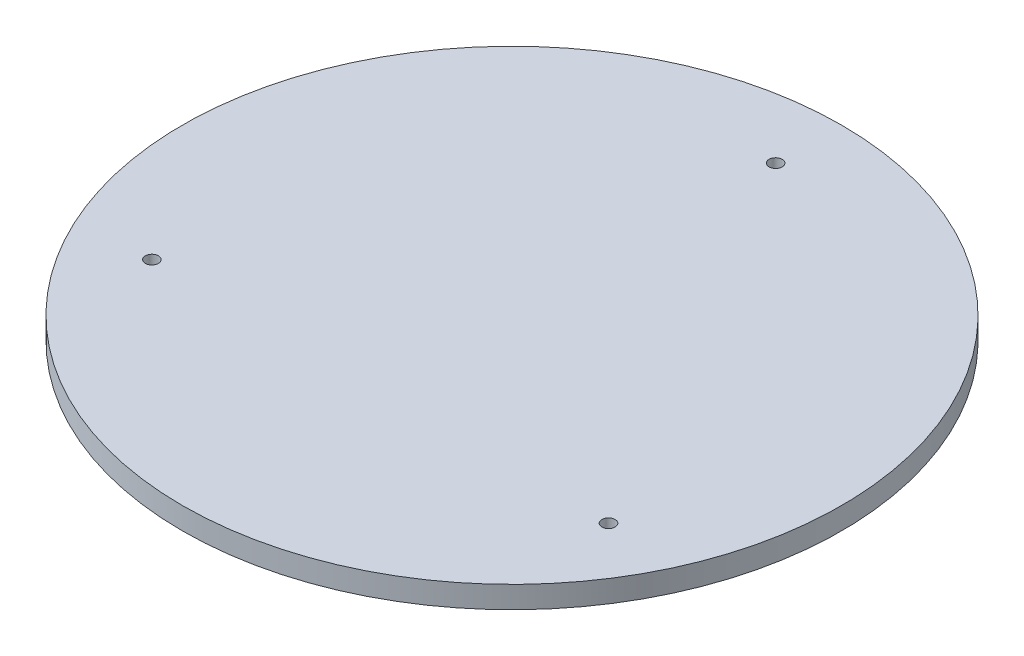
SolidWorks part; units mm, degrees
material "Alumina"
ref_plane "Front Plane" through (0, 0, 0) normal (0, 0, 1) x (1, 0, 0)
ref_plane "Top Plane" through (0, 0, 0) normal (0, 1, 0) x (1, 0, 0)
ref_plane "Right Plane" through (0, 0, 0) normal (1, 0, 0) x (0, 0, -1)
sketch "Sketch1" plane through (0, 0, 0) normal (0, 1, 0) x (1, 0, 0)
  circle A0 centre (0, 0) radius 75
  dimension "D1" = 150
extrude "Boss-Extrude1" add sketch "Sketch1" along normal blind 5
sketch "Sketch2" plane through (0, 5, 0) normal (0, 1, 0) x (1, 0, 0)
  line L0 (0, 0) -> (0, 75) construction
  line L1 (0, 0) -> (51.9615, -30) construction
  line L2 (51.9615, -30) -> (64.9519, -37.5) construction
  circle A0 centre (0, 60) radius 1.5
  circle A1 centre (0, 0) radius 75 construction
  circle A2 centre (51.9615, -30) radius 1.5
  circle A3 centre (-51.9615, -30) radius 1.5
  dimension "D1" = 3
  dimension "D2" = 15
  dimension "D4" = 120
  dimension "D5" = 15
  dimension "D3" = 3
extrude "Cut-Extrude1" cut sketch "Sketch2" against normal through all
